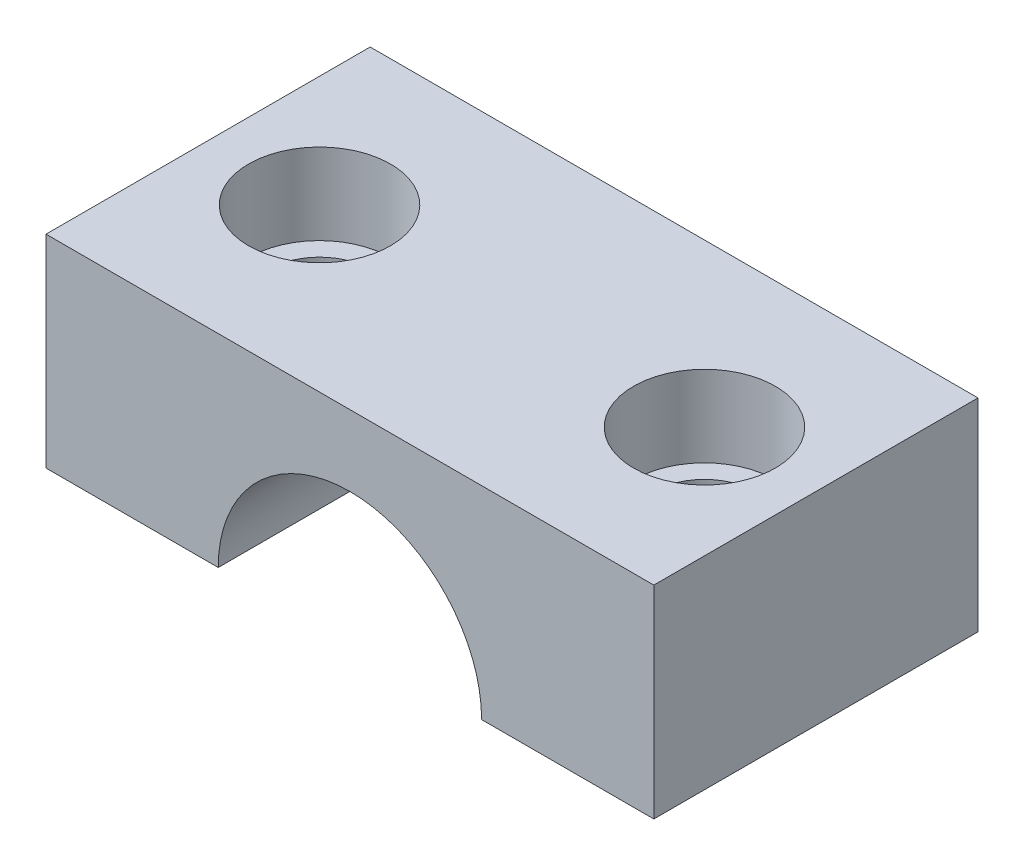
SolidWorks part; units mm, degrees
material "AISI 1015 Steel, Cold Drawn (SS)"
ref_plane "Front Plane" through (0, 0, 0) normal (0, 0, 1) x (1, 0, 0)
ref_plane "Top Plane" through (0, 0, 0) normal (0, 1, 0) x (1, 0, 0)
ref_plane "Right Plane" through (0, 0, 0) normal (1, 0, 0) x (0, 0, -1)
sketch "Sketch1" plane through (0, 0, 0) normal (0, 0, 1) x (1, 0, 0)
  line L0 (-13, 0) -> (-30, 0)
  line L1 (13, 0) -> (30, 0)
  line L2 (-30, 0) -> (-30, 20)
  line L3 (-30, 20) -> (30, 20)
  line L4 (30, 20) -> (30, 0)
  arc A0 (-13, 0) -> (13, 0) centre (0, 0) cw
  dimension "D1" = 26
  dimension "D2" = 60
  dimension "D3" = 20
extrude "Boss-Extrude1" add sketch "Sketch1" along normal blind 32
sketch "Sketch2" plane through (0, 20, 0) normal (0, 1, 0) x (1, 0, 0)
  line L0 (-30, -16) -> (30, -16) construction
  line L1 (-30, -32) -> (-30, 0) construction
  line L2 (30, -32) -> (30, 0) construction
  line L3 (-30, -8.1888) -> (-19, -8.1888) construction
  line L4 (30, -8.1888) -> (19, -8.1888) construction
  dimension "D1" = 11
  dimension "D2" = 11
hole_wizard "CBORE for M8 SHCS1" positions "Sketch5" profile "Sketch6" counterbore size "M8" standard "ANSI Metric" end condition through all
sketch "Sketch5" plane through (0, 20, 0) normal (0, 1, 0) x (1, 0, 0)
  line L0 (-30, -16) -> (30, -16) construction
  point P0 (-19, -16)
  point P4 (19, -16)
sketch "Sketch6" plane through (-19, 20, 16) normal (1, 0, 0) x (0, 0, 1)
  line L0 (0, 0) -> (0, 20)
  line L1 (0, 20) -> (5, 20)
  line L3 (5, 20) -> (5, 8)
  line L4 (5, 8) -> (7, 8)
  line L5 (7, 8) -> (7, 0)
  line L7 (7, 0) -> (0, 0)
  line L11 (0, -6.35) -> (0, 107.95) construction
  dimension "Thru Hole Dia." = 10
  dimension "Thru Hole Depth" = 20
  dimension "C'Bore Dia." = 14
  dimension "C'Bore Depth" = 8
